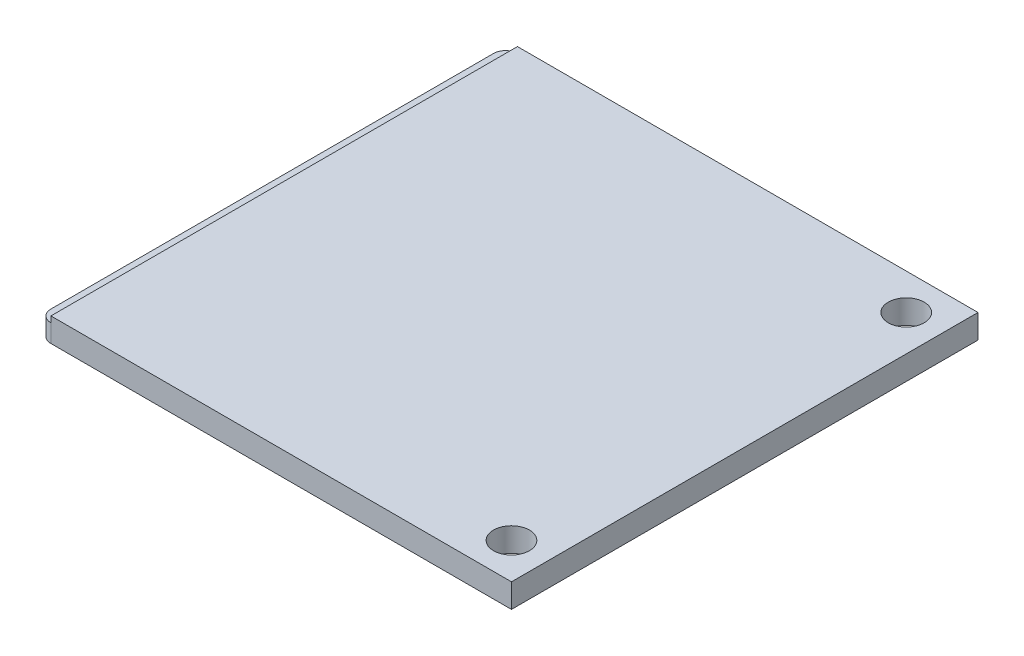
SolidWorks part; units mm, degrees
ref_plane "Ebene vorne" through (0, 0, 0) normal (0, 0, 1) x (1, 0, 0)
ref_plane "Ebene oben" through (0, 0, 0) normal (0, 1, 0) x (1, 0, 0)
ref_plane "Ebene rechts" through (0, 0, 0) normal (1, 0, 0) x (0, 0, -1)
sketch "Skizze1" plane through (0, 0, 0) normal (0, 1, 0) x (1, 0, 0)
  line L1 (0, 0) -> (39.5, 0)
  line L2 (0, 0) -> (0, -39)
  line L3 (0, -39) -> (39.5, -39)
  line L4 (39.5, 0) -> (39.5, -39)
  dimension "D1" = 39
  dimension "D2" = 39.5
extrude "Aufsatz-Linear austragen1" add sketch "Skizze1" along normal blind 2
hole_wizard "Ø3.0 (3) Durchmesser Bohrung1" positions "Skizze2" profile "Skizze3" hole size "Ø3.0" standard "ANSI Metric" end condition through all
sketch "Skizze2" plane through (0, 2, 0) normal (0, 1, 0) x (1, 0, 0)
  line L0 (39.5, -39) -> (39.5, 0) construction
  line L1 (39.5, 0) -> (0, 0) construction
  line L2 (0, -39) -> (39.5, -39) construction
  point P0 (36.5, -3)
  point P2 (36.5, -36)
  point P5 (0, 0)
  dimension "D1" = 3
  dimension "D2" = 3
  dimension "D3" = 3
  dimension "D4" = 3
sketch "Skizze3" plane through (36.5, 2, 3) normal (1, 0, 0) x (0, 0, 1)
  line L0 (0, 0) -> (0, 2)
  line L1 (0, 2) -> (1.5, 2)
  line L2 (1.5, 2) -> (1.5, 0)
  line L5 (1.5, 0) -> (0, 0)
  line L11 (0, -6.35) -> (0, 107.95) construction
  dimension "Bohrerdurchmesser" = 3
  dimension "Bohrungstiefe" = 2
sketch "Skizze4" plane through (0, 2, 0) normal (0, 1, 0) x (1, 0, 0)
  line L0 (0, -39) -> (39.5, -39) construction
  line L1 (0, 0) -> (1, 0)
  line L2 (0, 0) -> (0, -39)
  line L3 (0, -39) -> (1, -39)
  line L4 (1, 0) -> (1, -39)
  dimension "D1" = 1
extrude "Schnitt-Linear austragen1" cut sketch "Skizze4" against normal blind 0.5
fillet "Verrundung1" radius 1 2 edges at (0, 0.75, 0) (0, 0.75, 39)
